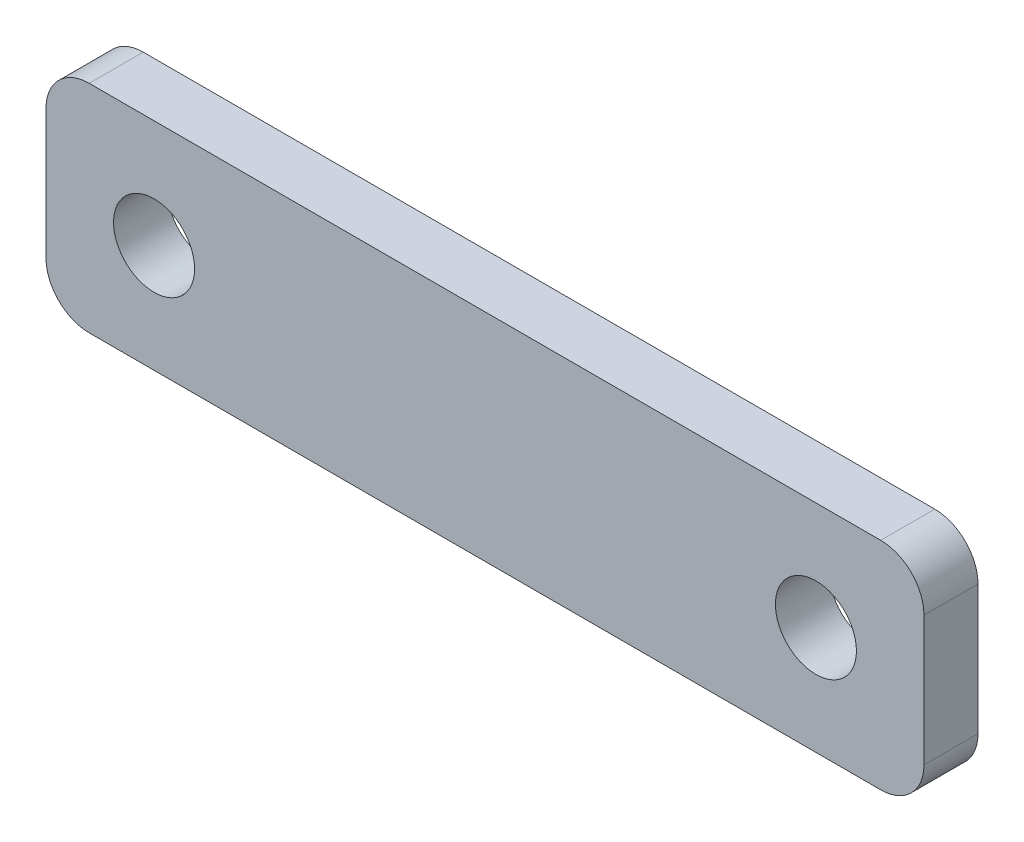
SolidWorks part; units mm, degrees
material "Alloy Steel"
ref_plane "Front Plane" through (0, 0, 0) normal (0, 0, 1) x (1, 0, 0)
ref_plane "Top Plane" through (0, 0, 0) normal (0, 1, 0) x (1, 0, 0)
ref_plane "Right Plane" through (0, 0, 0) normal (1, 0, 0) x (0, 0, -1)
other "Configuration Table"
sketch "Sketch1" plane through (0, 0, 0) normal (0, 0, 1) x (1, 0, 0)
  line L1 (0, 0) -> (103.1875, 0)
  line L2 (0, 0) -> (0, 25.4)
  line L3 (0, 25.4) -> (103.1875, 25.4)
  line L4 (103.1875, 0) -> (103.1875, 25.4)
  dimension "D1" = 103.1875
  dimension "D2" = 25.4
extrude "Boss-Extrude1" add sketch "Sketch1" against normal blind 6.35
fillet "Fillet1" radius 5.08 4 edges at (103.1875, 0, -3.175) (0, 0, -3.175) (0, 25.4, -3.175) (103.1875, 25.4, -3.175)
sketch "Sketch2" plane through (0, 0, 0) normal (0, 0, 1) x (1, 0, 0)
  line L0 (0, 20.32) -> (0, 5.08) construction
  line L1 (98.1075, 25.4) -> (5.08, 25.4) construction
  line L2 (103.1875, 5.08) -> (103.1875, 20.32) construction
  circle A0 centre (12.7, 12.7) radius 4.7625
  circle A1 centre (90.4875, 12.7) radius 4.7625
  dimension "D1" = 9.525
  dimension "D2" = 12.7
  dimension "D3" = 12.7
  dimension "D4" = 12.7
  dimension "D5" = 12.7
extrude "Cut-Extrude1" cut sketch "Sketch2" against normal through all
